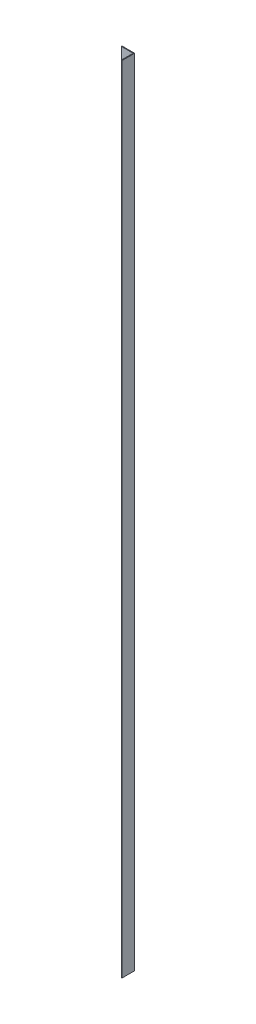
SolidWorks part; units mm, degrees
ref_plane "Front Plane" through (0, 0, 0) normal (0, 0, 1) x (1, 0, 0)
ref_plane "Top Plane" through (0, 0, 0) normal (0, 1, 0) x (1, 0, 0)
ref_plane "Right Plane" through (0, 0, 0) normal (1, 0, 0) x (0, 0, -1)
sketch "Sketch2" plane through (0, -750, 0) normal (0, -1, 0) x (1, 0, 0)
  line L1 (275, 169.5) -> (273.5, 169.5)
  line L2 (275, 169.5) -> (275, 143.5)
  line L3 (275, 143.5) -> (249, 143.5)
  line L4 (249, 145) -> (249, 143.5)
  line L5 (249, 145) -> (273.5, 145)
  line L6 (273.5, 145) -> (273.5, 169.5)
  dimension "D2" = 26
  dimension "D3" = 1.5
  dimension "D4" = 1.5
extrude "Boss-Extrude1" add sketch "Sketch2" against normal mid plane 1650
